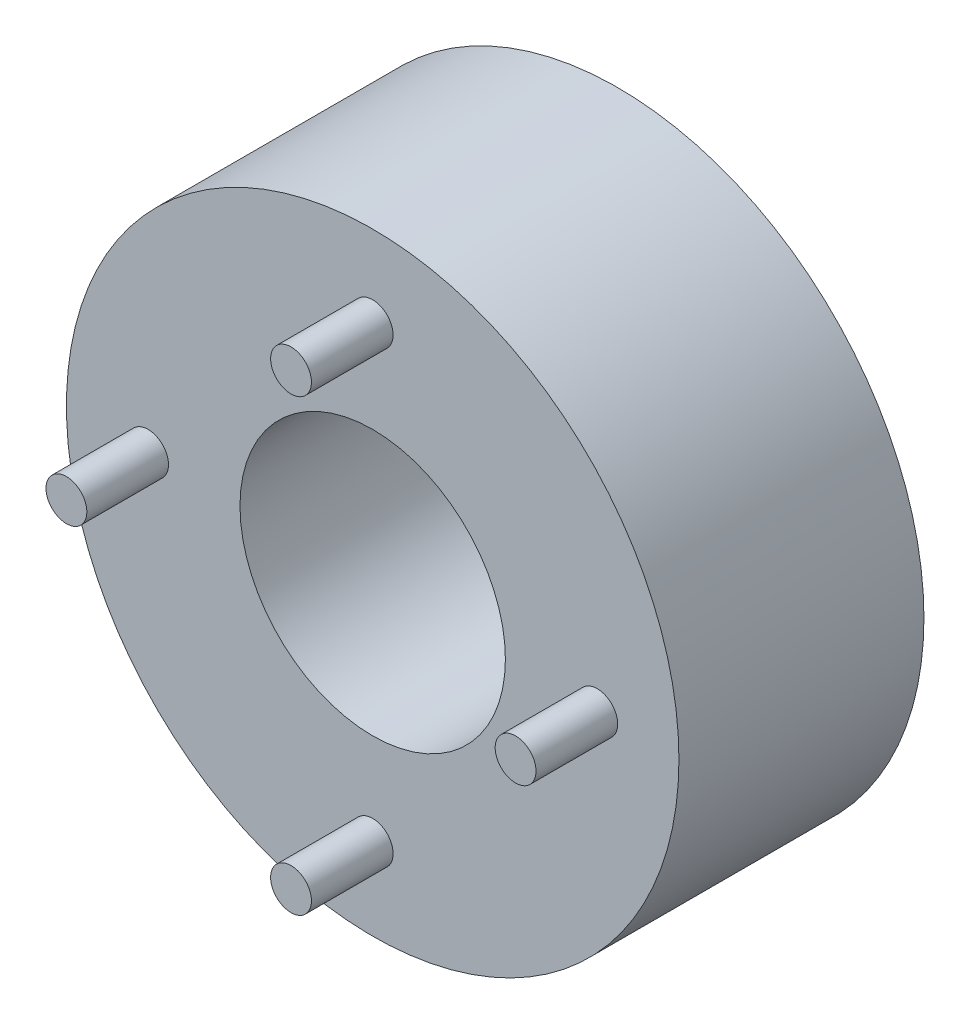
SolidWorks part; units mm, degrees
ref_plane "Płaszczyzna przednia" through (0, 0, 0) normal (0, 0, 1) x (1, 0, 0)
ref_plane "Płaszczyzna górna" through (0, 0, 0) normal (0, 1, 0) x (1, 0, 0)
ref_plane "Płaszczyzna prawa" through (0, 0, 0) normal (1, 0, 0) x (0, 0, -1)
sketch "Szkic1" plane through (0, 0, 0) normal (0, 0, 1) x (1, 0, 0)
  circle A0 centre (0, 0) radius 3.25
  circle A1 centre (0, 0) radius 7.5
  point P4 (13.8507, 0)
  dimension "D1" = 15
  dimension "D2" = 6.5
extrude "Dodanie-wyciągnięcie1" add sketch "Szkic1" along normal blind 4
sketch "Szkic2" plane through (0, 0, 4) normal (0, 0, 1) x (1, 0, 0)
  circle A0 centre (0, 0) radius 3.25
  circle A1 centre (0, 0) radius 7.5
  dimension "D1" = 6.5
extrude "Dodanie-wyciągnięcie2" add sketch "Szkic2" along normal blind 2
sketch "Szkic3" plane through (0, 0, 6) normal (0, 0, 1) x (1, 0, 0)
  line L0 (-7.5, 0) -> (-5, 0) construction
  line L1 (0, 7.5) -> (0, -7.5) construction
  line L2 (5.5, 0) -> (7.5, 0) construction
  line L3 (0, 0) -> (5, 0) construction
  circle A0 centre (0, 0) radius 7.5 construction
  circle A2 centre (0, 5.5) radius 0.5
  circle A3 centre (5.5, 0) radius 0.5
  circle A4 centre (0, -5.5) radius 0.5
  circle A5 centre (-5.5, 0) radius 0.5
  point P20 (0, 0)
  dimension "D2" = 4
extrude "Dodanie-wyciągnięcie3" add sketch "Szkic3" along normal blind 2
